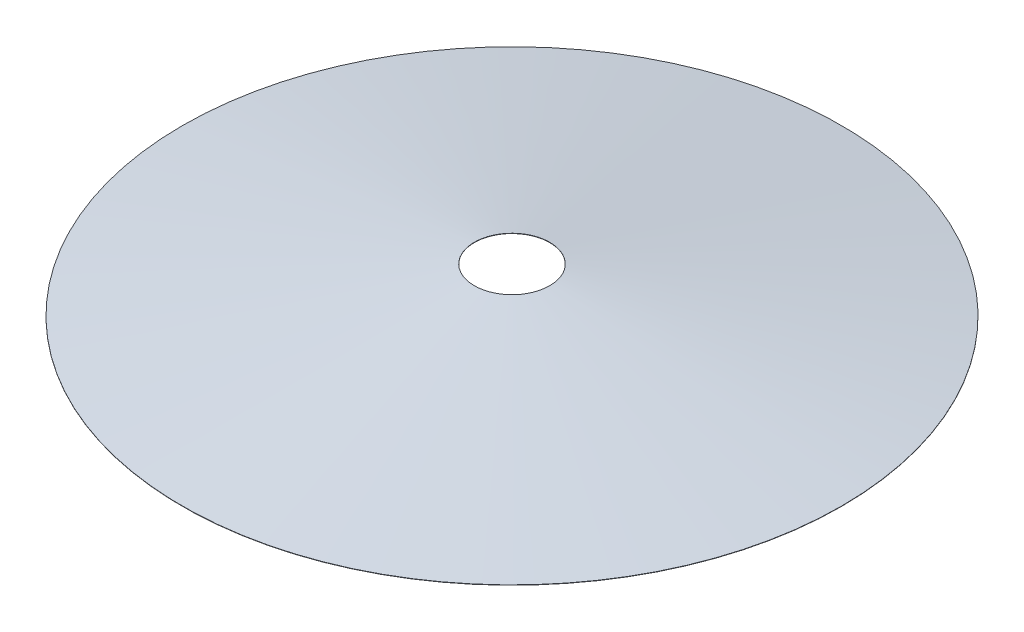
SolidWorks part; units mm, degrees
ref_plane "Front Plane" through (0, 0, 0) normal (0, 0, 1) x (1, 0, 0)
ref_plane "Top Plane" through (0, 0, 0) normal (0, 1, 0) x (1, 0, 0)
ref_plane "Right Plane" through (0, 0, 0) normal (1, 0, 0) x (0, 0, -1)
sketch "Sketch1" plane through (0, 0, 0) normal (0, 0, 1) x (1, 0, 0)
  line L6 (-1000, 154.2969) -> (49000, 154.2969) construction
  line L10 (0, 796) -> (0, 200) construction
  line L12 (0, 0) -> (-4400, 0) construction
  line L15 (-4374, 204) -> (-4374, 200)
  line L16 (0, 796) -> (-500, 796)
  line L17 (-500, 796) -> (-4374, 200)
  line L19 (0, 800) -> (-500, 800)
  line L20 (-500, 800) -> (-4374, 204)
  line L21 (0, 796) -> (0, 800)
  dimension "D1" = 154.2969
  dimension "D2" = 4
  dimension "D4" = 4400
revolve "Revolve1" add sketch "Sketch1" angle 360 about L10
sketch "Sketch2" plane through (0, 800, 0) normal (0, 1, 0) x (1, 0, 0)
  circle A0 centre (0, 0) radius 500
extrude "Cut-Extrude1" cut sketch "Sketch2" against normal through all both and the other way through all
